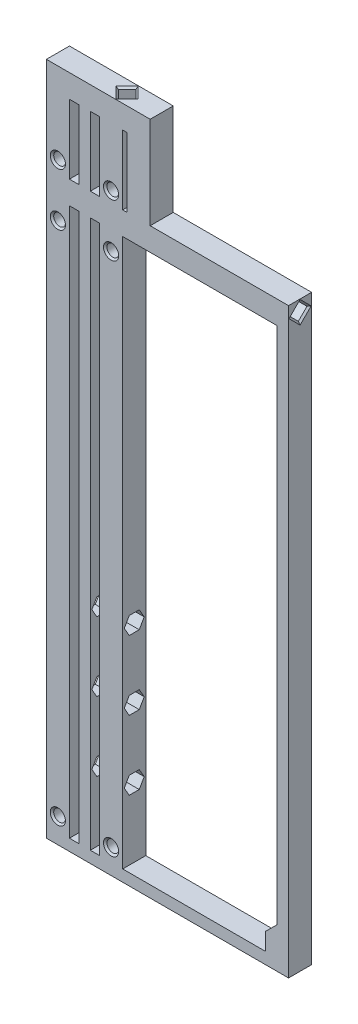
SolidWorks part; units mm, degrees
ref_plane "Front Plane" through (0, 0, 0) normal (0, 0, 1) x (1, 0, 0)
ref_plane "Top Plane" through (0, 0, 0) normal (0, 1, 0) x (1, 0, 0)
ref_plane "Right Plane" through (0, 0, 0) normal (1, 0, 0) x (0, 0, -1)
sketch "Sketch1" plane through (0, 0, 0) normal (0, 0, 1) x (1, 0, 0)
  line L0 (35.9833, -119.5917) -> (35.9833, -113.2417)
  line L1 (-6.35, 123.825) -> (-44.45, 123.825)
  line L2 (44.45, 89.9583) -> (44.45, -123.825)
  line L3 (44.45, -123.825) -> (-44.45, -123.825)
  line L4 (-14.8167, 115.3583) -> (-14.8167, 89.9583)
  line L7 (35.9833, -119.5917) -> (-16.4333, -119.5917)
  line L9 (35.9833, -113.2417) -> (40.2167, -109.0083)
  line L12 (-6.35, 123.825) -> (-6.35, 89.9583)
  line L14 (-14.8167, 115.3583) -> (-16.4333, 115.3583)
  line L16 (-35.9833, 115.3583) -> (-35.9833, 89.9583)
  line L18 (-35.9833, -119.5917) -> (-32.5583, -119.5917)
  line L19 (-28.325, 89.9583) -> (-24.9, 89.9583)
  line L20 (-44.45, 123.825) -> (-44.45, -123.825)
  line L21 (-35.9833, 89.9583) -> (-32.5583, 89.9583)
  line L22 (-35.9833, 81.4917) -> (-32.5583, 81.4917)
  line L23 (-32.5583, 81.4917) -> (-32.5583, -119.5917)
  line L26 (40.2167, 81.4917) -> (40.2167, -109.0083)
  line L27 (-6.35, 89.9583) -> (44.45, 89.9583)
  line L28 (-16.4333, 81.4917) -> (40.2167, 81.4917)
  line L29 (-35.9833, 81.4917) -> (-35.9833, -119.5917)
  line L30 (-24.9, 115.3583) -> (-24.9, 89.9583)
  line L31 (-16.4333, 115.3583) -> (-16.4333, 89.9583)
  line L32 (-24.9, 115.3583) -> (-28.325, 115.3583)
  line L33 (-16.4333, 89.9583) -> (-14.8167, 89.9583)
  line L34 (-24.9, 81.4917) -> (-24.9, -119.5917)
  line L35 (-16.4333, -119.5917) -> (-16.4333, 81.4917)
  line L36 (-32.5583, 115.3583) -> (-32.5583, 89.9583)
  line L38 (-28.325, 89.9583) -> (-28.325, 115.3583)
  line L39 (-32.5583, 115.3583) -> (-35.9833, 115.3583)
  line L40 (-28.325, -119.5917) -> (-28.325, 81.4917)
  line L41 (-28.325, 81.4917) -> (-24.9, 81.4917)
  line L42 (-28.325, -119.5917) -> (-24.9, -119.5917)
  line L43 (-35.9833, -119.5917) -> (-44.45, -119.5917) construction
  line L44 (-24.9, -119.5917) -> (-16.4333, -119.5917) construction
  line L45 (-44.45, -119.5917) -> (-35.9833, -119.5917) construction
  line L46 (-24.9, -119.5917) -> (-16.4333, -119.5917) construction
  line L47 (-32.5583, -119.5917) -> (-28.325, -119.5917) construction
  line L48 (-35.9833, 89.9583) -> (-35.9833, 81.4917) construction
  line L49 (-14.8167, 89.9583) -> (-6.35, 89.9583) construction
  line L50 (-35.9833, -119.5917) -> (-44.45, -119.5917) construction
  line L51 (40.2167, -109.0083) -> (44.45, -109.0083) construction
  line L52 (-35.9833, 115.3583) -> (-35.9833, 123.825) construction
  point P4 (0, -123.825)
  point P11 (-44.45, 0)
  dimension "D2" = 247.65
  dimension "D3" = 4.2333
  dimension "D4" = 8.4667
  dimension "D5" = 88.9
  dimension "D6" = 8.4667
  dimension "D7" = 33.8667
  dimension "D8" = 45
  dimension "D9" = 6.35
  dimension "D10" = 56.65
  dimension "D11" = 38.1
  dimension "D12" = 4.2333
extrude "Boss-Extrude1" add sketch "Sketch1" along normal blind 8.4667
sketch "Sketch4" plane through (-44.45, 0, 0) normal (-1, 0, 0) x (0, 0, 1)
  line L0 (1.0583, 85.725) -> (4.2333, 88.9)
  line L1 (1.0583, 85.725) -> (4.2333, 82.55)
  line L2 (4.2333, 88.9) -> (7.4083, 85.725)
  line L3 (4.2333, 82.55) -> (7.4083, 85.725)
  line L4 (1.0583, 85.725) -> (7.4083, 85.725) construction
  line L5 (4.2333, 88.9) -> (4.2333, 82.55) construction
  line L6 (8.4667, 123.825) -> (0, 123.825) construction
  line L7 (1.0583, 119.5917) -> (4.2333, 122.7667)
  line L8 (1.0583, 119.5917) -> (4.2333, 116.4167)
  line L9 (4.2333, 122.7667) -> (7.4083, 119.5917)
  line L10 (4.2333, 116.4167) -> (7.4083, 119.5917)
  line L11 (1.0583, 119.5917) -> (7.4083, 119.5917) construction
  line L12 (4.2333, 122.7667) -> (4.2333, 116.4167) construction
  line L13 (8.4667, 123.825) -> (0, 123.825) construction
  point P1 (4.2333, 85.725)
  point P3 (4.2333, 123.825)
  point P9 (4.2333, 119.5917)
  dimension "D1" = 6.35
  dimension "D2" = 4.2333
  dimension "D3" = 33.8667
extrude "rear pins" cut sketch "Sketch4" against normal blind 6.35
sketch "Sketch5" plane through (0, -123.825, 0) normal (0, -1, 0) x (1, 0, 0)
  line L0 (-23.8417, 4.2333) -> (-20.6667, 7.4083)
  line L1 (-23.8417, 4.2333) -> (-20.6667, 1.0583)
  line L2 (-20.6667, 7.4083) -> (-17.4917, 4.2333)
  line L3 (-20.6667, 1.0583) -> (-17.4917, 4.2333)
  line L4 (-23.8417, 4.2333) -> (-17.4917, 4.2333) construction
  line L5 (-20.6667, 7.4083) -> (-20.6667, 1.0583) construction
  line L6 (37.0417, 4.2333) -> (40.2167, 7.4083)
  line L7 (37.0417, 4.2333) -> (40.2167, 1.0583)
  line L8 (40.2167, 7.4083) -> (43.3917, 4.2333)
  line L9 (40.2167, 1.0583) -> (43.3917, 4.2333)
  line L10 (37.0417, 4.2333) -> (43.3917, 4.2333) construction
  line L11 (40.2167, 7.4083) -> (40.2167, 1.0583) construction
  line L12 (-24.9, 8.4667) -> (-24.9, 0) construction
  line L13 (44.45, 8.4667) -> (44.45, 0) construction
  line L14 (-43.3917, 4.2333) -> (-40.2167, 7.4083)
  line L15 (-43.3917, 4.2333) -> (-40.2167, 1.0583)
  line L16 (-40.2167, 7.4083) -> (-37.0417, 4.2333)
  line L17 (-40.2167, 1.0583) -> (-37.0417, 4.2333)
  line L18 (-43.3917, 4.2333) -> (-37.0417, 4.2333) construction
  line L19 (-40.2167, 7.4083) -> (-40.2167, 1.0583) construction
  line L23 (-35.9833, 8.4667) -> (-35.9833, 0) construction
  point P0 (44.45, 4.2333)
  point P1 (-20.6667, 4.2333)
  point P2 (40.2167, 4.2333)
  point P16 (-40.2167, 4.2333)
  dimension "D1" = 6.35
  dimension "D2" = 4.2333
  dimension "D3" = 4.2333
  dimension "D4" = 4.2333
  dimension "D5" = 6.35
extrude "bottom pins" cut sketch "Sketch5" against normal blind 6.35
sketch "Sketch2" plane through (44.45, 0, 0) normal (1, 0, 0) x (0, 0, -1)
  line L0 (-7.4083, 85.725) -> (-4.2333, 88.9)
  line L1 (-7.4083, 85.725) -> (-4.2333, 82.55)
  line L2 (-4.2333, 88.9) -> (-1.0583, 85.725)
  line L3 (-4.2333, 82.55) -> (-1.0583, 85.725)
  line L4 (-7.4083, 85.725) -> (-1.0583, 85.725) construction
  line L5 (-4.2333, 88.9) -> (-4.2333, 82.55) construction
  line L10 (-8.4667, 89.9583) -> (0, 89.9583) construction
  line L14 (-8.4667, 123.825) -> (0, 123.825) construction
  point P1 (-4.2333, 85.725)
  point P15 (-4.2333, 123.825)
  dimension "D1" = 4.2333
  dimension "D3" = 6.35
extrude "front pins" cut sketch "Sketch2" against normal blind 6.35
sketch "Sketch7" plane through (0, 0, 0) normal (0, 0, -1) x (-1, 0, 0)
  line L0 (7.4083, 85.725) -> (10.5833, 88.9)
  line L1 (7.4083, 85.725) -> (10.5833, 82.55)
  line L2 (10.5833, 88.9) -> (13.7583, 85.725)
  line L3 (10.5833, 82.55) -> (13.7583, 85.725)
  line L4 (7.4083, 85.725) -> (13.7583, 85.725) construction
  line L5 (10.5833, 88.9) -> (10.5833, 82.55) construction
  line L6 (-40.2167, 81.4917) -> (16.4333, 81.4917) construction
  line L7 (6.35, 123.825) -> (44.45, 123.825) construction
  line L8 (10.5833, 122.7667) -> (13.7583, 119.5917)
  line L9 (10.5833, 122.7667) -> (7.4083, 119.5917)
  line L10 (13.7583, 119.5917) -> (10.5833, 116.4167)
  line L11 (7.4083, 119.5917) -> (10.5833, 116.4167)
  line L12 (10.5833, 122.7667) -> (10.5833, 116.4167) construction
  line L13 (13.7583, 119.5917) -> (7.4083, 119.5917) construction
  line L14 (6.35, 123.825) -> (6.35, 89.9583) construction
  point P1 (10.5833, 85.725)
  point P10 (10.5833, 119.5917)
  dimension "D1" = 6.35
  dimension "D2" = 4.2333
  dimension "D3" = 4.2333
  dimension "D4" = 4.2333
extrude "right pins" cut sketch "Sketch7" against normal blind 6.35
sketch "Sketch14" plane through (0, 123.825, 0) normal (0, 1, 0) x (1, 0, 0)
  line L0 (-22.225, -4.2333) -> (-19.05, -1.0583)
  line L1 (-22.225, -4.2333) -> (-19.05, -7.4083)
  line L2 (-19.05, -1.0583) -> (-15.875, -4.2333)
  line L3 (-19.05, -7.4083) -> (-15.875, -4.2333)
  line L4 (-22.225, -4.2333) -> (-15.875, -4.2333) construction
  line L5 (-19.05, -1.0583) -> (-19.05, -7.4083) construction
  line L6 (-6.35, 0) -> (-44.45, 0) construction
  line L7 (-6.35, -8.4667) -> (-6.35, 0) construction
  point P1 (-19.05, -4.2333)
  dimension "D1" = 6.35
  dimension "D2" = 12.7
  dimension "D3" = 4.2333
extrude "Cut-Extrude1" cut sketch "Sketch14" against normal blind 6.35
chamfer "Chamfer3" distance 0.635 angle 45 72 edges at (-38.1, 87.3125, 2.6458) (-38.1, 87.3125, 5.8208) (-38.1, 84.1375, 5.8208) (-38.1, 84.1375, 2.6458) (38.1, 87.3125, 5.8208) (38.1, 87.3125, 2.6458) (38.1, 84.1375, 2.6458) (38.1, 84.1375, 5.8208) (-8.9958, 87.3125, 6.35) (-12.1708, 87.3125, 6.35) (-12.1708, 84.1375, 6.35) (-8.9958, 84.1375, 6.35) (-12.1708, 121.1792, 6.35) (-12.1708, 118.0042, 6.35) (-8.9958, 118.0042, 6.35) (-8.9958, 121.1792, 6.35) (-38.1, 121.1792, 2.6458) (-38.1, 121.1792, 5.8208) (-38.1, 118.0042, 5.8208) (-38.1, 118.0042, 2.6458) (-44.45, 118.0042, 2.6458) (-44.45, 118.0042, 5.8208) (-44.45, 121.1792, 5.8208) (-44.45, 121.1792, 2.6458) (-44.45, 84.1375, 5.8208) (-44.45, 87.3125, 5.8208) (-44.45, 87.3125, 2.6458) (-44.45, 84.1375, 2.6458) (44.45, 84.1375, 5.8208) (44.45, 84.1375, 2.6458) (44.45, 87.3125, 2.6458) (44.45, 87.3125, 5.8208) (-12.1708, 84.1375, 0) (-8.9958, 84.1375, 0) (-8.9958, 87.3125, 0) (-12.1708, 87.3125, 0) (-8.9958, 118.0042, 0) (-12.1708, 118.0042, 0) (-12.1708, 121.1792, 0) (-8.9958, 121.1792, 0) (-22.2542, -117.475, 5.8208) (-19.0792, -117.475, 5.8208) (-19.0792, -117.475, 2.6458) (-22.2542, -117.475, 2.6458) (38.6292, -117.475, 5.8208) (41.8042, -117.475, 5.8208) (41.8042, -117.475, 2.6458) (38.6292, -117.475, 2.6458) (-22.2542, -123.825, 2.6458) (-19.0792, -123.825, 2.6458) (-19.0792, -123.825, 5.8208) (-22.2542, -123.825, 5.8208) (38.6292, -123.825, 2.6458) (41.8042, -123.825, 2.6458) (41.8042, -123.825, 5.8208) (38.6292, -123.825, 5.8208) (-41.8042, -117.475, 5.8208) (-38.6292, -117.475, 5.8208) (-38.6292, -117.475, 2.6458) (-41.8042, -117.475, 2.6458) (-38.6292, -123.825, 2.6458) (-38.6292, -123.825, 5.8208) (-41.8042, -123.825, 5.8208) (-41.8042, -123.825, 2.6458) (-20.6375, 117.475, 2.6458) (-17.4625, 117.475, 2.6458) (-17.4625, 117.475, 5.8208) (-20.6375, 117.475, 5.8208) (-20.6375, 123.825, 5.8208) (-17.4625, 123.825, 5.8208) (-17.4625, 123.825, 2.6458) (-20.6375, 123.825, 2.6458)
sketch "Sketch11" plane through (0, 0, 8.4667) normal (0, 0, 1) x (1, 0, 0)
  point P0 (-40.243, 74.63)
  point P1 (-40.251, -114.8)
  point P5 (-40.243, 93.98)
  point P7 (-20.701, 93.98)
  point P9 (-20.701, 74.63)
  point P11 (-20.701, -114.8)
  point P13 (-40.243, 74.63)
  point P14 (-40.243, 93.98)
  point P15 (-20.701, 93.98)
  point P16 (0, 0)
  point P17 (0, 0)
  point P18 (0, 0)
  point P19 (0, 0)
hole_wizard "#18 (0.1695) Diameter Hole1" positions "Sketch11" profile "Sketch13" hole size "#18" standard "ANSI Inch" end condition through all
sketch "Sketch13" plane through (-40.243, 74.63, 8.4667) normal (1, 0, 0) x (0, -1, 0)
  line L0 (0, 0) -> (0, 8.4667)
  line L1 (0, 8.4667) -> (2.1526, 8.4667)
  line L2 (2.1526, 8.4667) -> (2.1526, 0.635)
  line L3 (2.1526, 0.635) -> (2.7876, 0)
  line L5 (2.7876, 0) -> (0, 0)
  line L6 (-2.1526, 0.635) -> (-2.7876, 0) construction
  line L11 (0, -6.35) -> (0, 107.95) construction
  dimension "Thru Hole Dia." = 4.3053
  dimension "Thru Hole Depth" = 8.4667
  dimension "Near C'Sink Dia." = 5.5753
  dimension "Near C'Sink Angle" = 90
sketch "Sketch15" plane through (-16.4333, 0, 0) normal (1, 0, 0) x (0, 0, -1)
  line L0 (-8.4667, -119.5917) -> (0, -119.5917) construction
  line L1 (-2.4002, -97.3667) -> (-0.5672, -94.1917)
  line L2 (-0.5672, -94.1917) -> (-2.4002, -91.0167)
  line L3 (-2.4002, -91.0167) -> (-6.0664, -91.0167)
  line L4 (-6.0664, -91.0167) -> (-7.8995, -94.1917)
  line L5 (-7.8995, -94.1917) -> (-6.0664, -97.3667)
  line L6 (-6.0664, -97.3667) -> (-2.4002, -97.3667)
  line L7 (-2.4002, -71.9667) -> (-0.5672, -68.7917)
  line L8 (-0.5672, -68.7917) -> (-2.4002, -65.6167)
  line L9 (-2.4002, -65.6167) -> (-6.0664, -65.6167)
  line L10 (-6.0664, -65.6167) -> (-7.8995, -68.7917)
  line L11 (-7.8995, -68.7917) -> (-6.0664, -71.9667)
  line L12 (-6.0664, -71.9667) -> (-2.4002, -71.9667)
  line L14 (-2.4002, -46.5667) -> (-0.5672, -43.3917)
  line L15 (-0.5672, -43.3917) -> (-2.4002, -40.2167)
  line L16 (-2.4002, -40.2167) -> (-6.0664, -40.2167)
  line L17 (-6.0664, -40.2167) -> (-7.8995, -43.3917)
  line L18 (-7.8995, -43.3917) -> (-6.0664, -46.5667)
  line L19 (-6.0664, -46.5667) -> (-2.4002, -46.5667)
  circle A0 centre (-4.2333, -94.1917) radius 3.175 construction
  circle A1 centre (-4.2333, -68.7917) radius 3.175 construction
  circle A2 centre (-4.2333, -43.3917) radius 3.175 construction
  dimension "D4" = 6.35
  dimension "D1" = 25.4
  dimension "D2" = 25.4
  dimension "D3" = 25.4
extrude "Cut-Extrude2" cut sketch "Sketch15" against normal up to surface (16.125 mm away) up to face at (-32.5583, -19.05, 4.2333)
